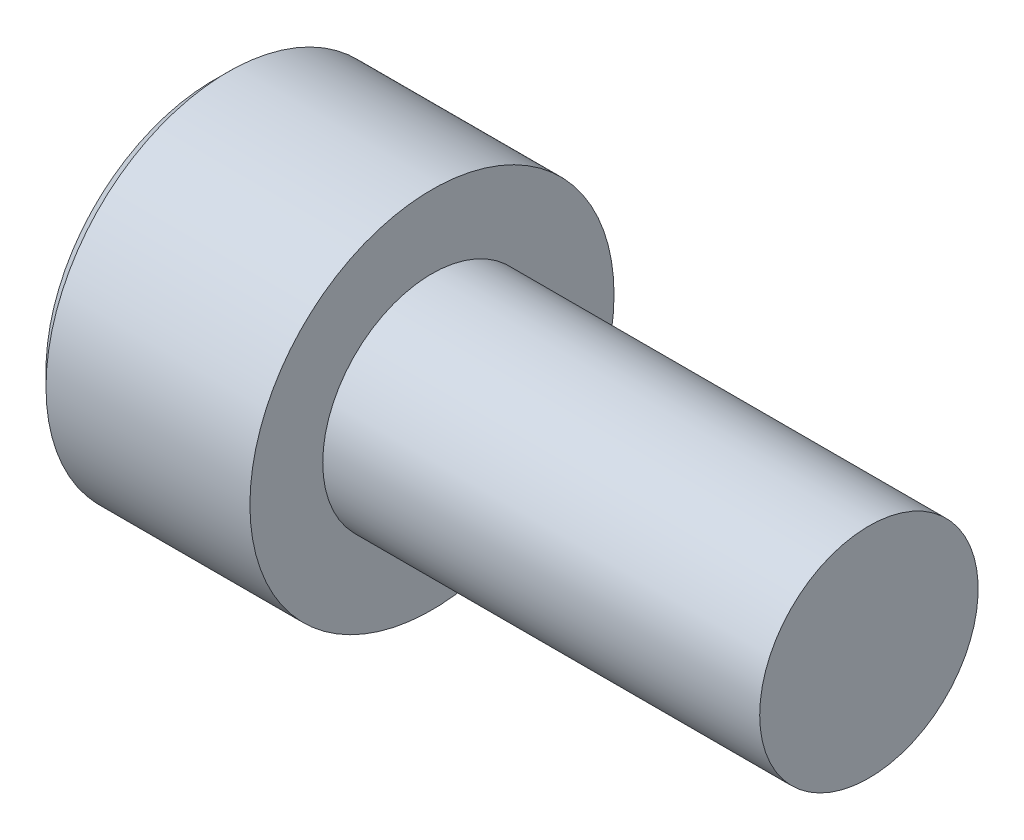
SolidWorks part; units mm, degrees
ref_plane "Front Plane" through (0, 0, 0) normal (0, 0, 1) x (1, 0, 0)
ref_plane "Top Plane" through (0, 0, 0) normal (0, 1, 0) x (1, 0, 0)
ref_plane "Right Plane" through (0, 0, 0) normal (1, 0, 0) x (0, 0, -1)
sketch "Sketch1" plane through (0, 0, 0) normal (0, 0, 1) x (1, 0, 0)
  line L0 (-6, 0) -> (12, 0) construction
  line L1 (-6, 0) -> (12, 0)
  line L2 (12, 0) -> (12, 3)
  line L3 (12, 3) -> (0, 3)
  line L4 (0, 3) -> (0, 5)
  line L5 (0, 5) -> (-6, 5)
  line L6 (-6, 5) -> (-6, 0)
  dimension "FIX_1" = 12
  dimension "FIX_3" = 10
  dimension "FIX_4" = 6
  dimension "FIX_2" = 6
revolve "Revolve1" add sketch "Sketch1" angle 360 about L0
cosmetic thread "Thread1" parameters "NFIX_1"=4.917
sketch "Sketch2" plane through (0, 0, 0) normal (0, 0, 1) x (1, 0, 0)
  line L0 (-6, 0) -> (-1.5566, 0)
  line L1 (-1.5566, 0) -> (-3, 2.5)
  line L2 (-3, 2.5) -> (-6, 2.5)
  line L3 (-6, 2.5) -> (-6, 0)
  line L4 (-1.5566, 0) -> (0, 0) construction
  line L5 (-6, 0) -> (12, 0) construction
  dimension "FIX_6" = 60
  dimension "FIX_8" = 5
  dimension "FIX_7" = 3
revolve "Cut-Revolve1" cut sketch "Sketch2" angle 360 about L4
sketch "Sketch3" plane through (-6, 0, 0) normal (-1, 0, 0) x (0, 0, 1)
  line L1 (2.8868, 0) -> (1.4434, 2.5)
  line L2 (1.4434, 2.5) -> (-1.4434, 2.5)
  line L3 (-1.4434, 2.5) -> (-2.8868, 0)
  line L4 (-2.8868, 0) -> (-1.4434, -2.5)
  line L5 (-1.4434, -2.5) -> (1.4434, -2.5)
  line L6 (1.4434, -2.5) -> (2.8868, 0)
  circle A0 centre (0, 0) radius 2.5 construction
  dimension "FIX_10" = 5
extrude "Cut-Extrude1" cut sketch "Sketch3" against normal blind 3
chamfer "Chamfer1" distance 0.4 1 edges at (-6, 0, 5)
